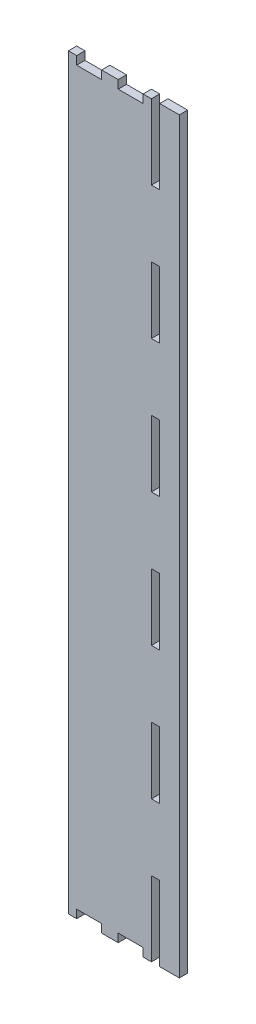
SolidWorks part; units mm, degrees
ref_plane "Front Plane" through (0, 0, 0) normal (0, 0, 1) x (1, 0, 0)
ref_plane "Top Plane" through (0, 0, 0) normal (0, 1, 0) x (1, 0, 0)
ref_plane "Right Plane" through (0, 0, 0) normal (1, 0, 0) x (0, 0, -1)
sketch "Sketch1" plane through (0, 0, 0) normal (0, 0, 1) x (1, 0, 0)
  line L0 (191.6857, 206.3418) -> (186.6857, 206.3418) construction
  line L4 (191.6857, -198.6582) -> (186.6857, -198.6582) construction
  line L6 (186.6857, -158.6582) -> (191.6857, -158.6582) construction
  line L8 (191.6857, -118.6582) -> (186.6857, -118.6582) construction
  line L10 (186.6857, -78.6582) -> (191.6857, -78.6582) construction
  line L12 (191.6857, -38.6582) -> (186.6857, -38.6582) construction
  line L14 (186.6857, 1.3418) -> (191.6857, 1.3418) construction
  line L16 (191.6857, 41.3418) -> (186.6857, 41.3418) construction
  line L18 (186.6857, 81.3418) -> (191.6857, 81.3418) construction
  line L40 (191.6857, 121.3418) -> (186.6857, 121.3418) construction
  line L41 (203.4867, 206.3418) -> (191.6857, 206.3418)
  line L42 (203.4867, 206.3418) -> (203.4867, -243.6582)
  line L43 (203.4867, -243.6582) -> (191.6857, -243.6582)
  line L46 (186.6857, 161.3418) -> (191.6857, 161.3418) construction
  line L48 (186.6857, -198.6582) -> (186.6857, -243.6582)
  line L50 (191.6857, -243.6582) -> (191.6857, -198.6582)
  line L51 (191.6857, -198.6582) -> (186.6857, -198.6582)
  line L52 (186.6857, -118.6582) -> (186.6857, -158.6582)
  line L53 (186.6857, -158.6582) -> (191.6857, -158.6582)
  line L54 (191.6857, -158.6582) -> (191.6857, -118.6582)
  line L55 (191.6857, -118.6582) -> (186.6857, -118.6582)
  line L56 (186.6857, -38.6582) -> (186.6857, -78.6582)
  line L57 (186.6857, -78.6582) -> (191.6857, -78.6582)
  line L58 (191.6857, -78.6582) -> (191.6857, -38.6582)
  line L59 (191.6857, -38.6582) -> (186.6857, -38.6582)
  line L60 (186.6857, 41.3418) -> (186.6857, 1.3418)
  line L61 (186.6857, 1.3418) -> (191.6857, 1.3418)
  line L62 (191.6857, 1.3418) -> (191.6857, 41.3418)
  line L63 (191.6857, 41.3418) -> (186.6857, 41.3418)
  line L64 (186.6857, 121.3418) -> (186.6857, 81.3418)
  line L65 (186.6857, 81.3418) -> (191.6857, 81.3418)
  line L66 (191.6857, 81.3418) -> (191.6857, 121.3418)
  line L67 (191.6857, 121.3418) -> (186.6857, 121.3418)
  line L69 (186.6857, 161.3418) -> (191.6857, 161.3418)
  line L70 (191.6857, 161.3418) -> (191.6857, 206.3418)
  line L72 (186.6857, 206.3418) -> (181.6857, 206.3418)
  line L73 (186.6857, -243.6582) -> (181.6857, -243.6582)
  line L75 (186.6857, 206.3418) -> (181.6857, 206.3418) construction
  line L76 (181.6857, 206.3418) -> (181.6857, 201.3418) construction
  line L78 (186.6857, 201.3418) -> (186.6857, 206.3418) construction
  line L79 (166.6857, 206.3418) -> (156.6857, 206.3418) construction
  line L80 (156.6857, 206.3418) -> (156.6857, 201.3418) construction
  line L82 (166.6857, 201.3418) -> (166.6857, 206.3418) construction
  line L83 (141.6857, 206.3418) -> (136.6857, 206.3418) construction
  line L84 (136.6857, 206.3418) -> (136.6857, 201.3418) construction
  line L86 (141.6857, 201.3418) -> (141.6857, 206.3418) construction
  line L87 (186.6857, 206.3418) -> (181.6857, 206.3418)
  line L88 (181.6857, 206.3418) -> (181.6857, 201.3418)
  line L90 (186.6857, 161.3418) -> (186.6857, 206.3418)
  line L91 (166.6857, 206.3418) -> (156.6857, 206.3418)
  line L92 (156.6857, 206.3418) -> (156.6857, 201.3418)
  line L94 (166.6857, 201.3418) -> (166.6857, 206.3418)
  line L95 (141.6857, 206.3418) -> (136.6857, 206.3418)
  line L96 (136.6857, 206.3418) -> (136.6857, -243.6582)
  line L98 (141.6857, 201.3418) -> (141.6857, 206.3418)
  line L99 (166.6857, 201.3418) -> (181.6857, 201.3418)
  line L100 (156.6857, 201.3418) -> (141.6857, 201.3418)
  line L101 (166.6857, 206.3418) -> (133.4867, 206.3418)
  line L102 (181.6857, -238.6582) -> (166.6857, -238.6582) construction
  line L103 (166.6857, -238.6582) -> (166.6857, -243.6582) construction
  line L105 (181.6857, -243.6582) -> (181.6857, -238.6582) construction
  line L106 (156.6857, -238.6582) -> (141.6857, -238.6582) construction
  line L107 (141.6857, -238.6582) -> (141.6857, -243.6582) construction
  line L109 (156.6857, -243.6582) -> (156.6857, -238.6582) construction
  line L110 (181.6857, -238.6582) -> (166.6857, -238.6582)
  line L111 (166.6857, -238.6582) -> (166.6857, -243.6582)
  line L113 (181.6857, -243.6582) -> (181.6857, -238.6582)
  line L114 (156.6857, -238.6582) -> (141.6857, -238.6582)
  line L115 (141.6857, -238.6582) -> (141.6857, -243.6582)
  line L117 (156.6857, -243.6582) -> (156.6857, -238.6582)
  line L118 (141.6857, -243.6582) -> (136.6857, -243.6582)
  line L119 (166.6857, -243.6582) -> (156.6857, -243.6582)
extrude "Boss-Extrude1" add sketch "Sketch1" along normal blind 5 contours L92 L100 L98 L95 L96 L73 L48 L51 L50 L43 L42 L41 L70 L69 L90 L72 L88 L99 L94 L91 L55 L54 L53 L52 L59 L58 L57 L56 L63 L62 L61 L60 L67 L66 L65 L64
